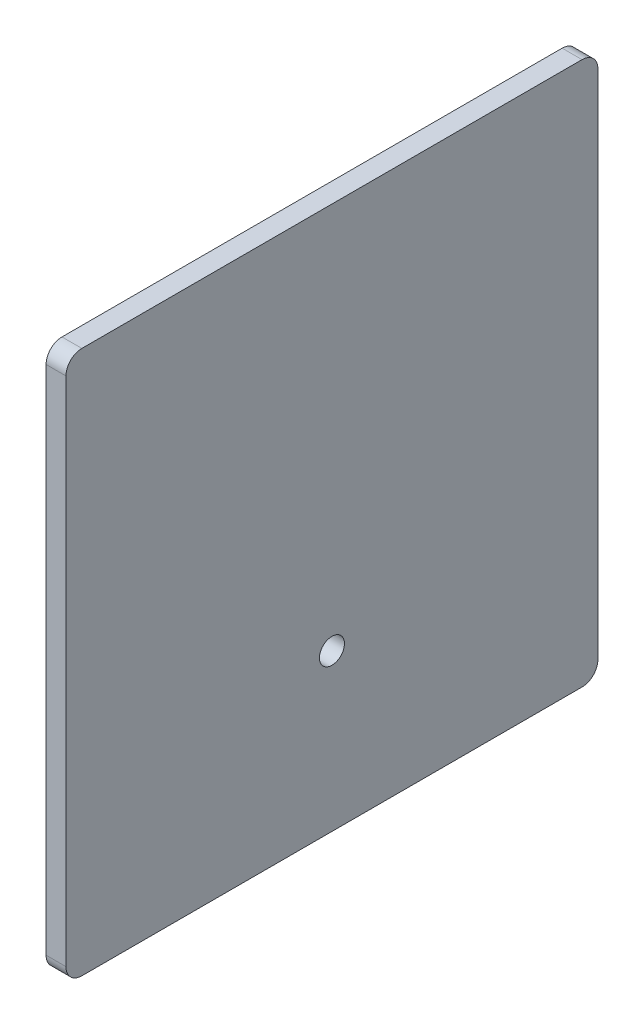
SolidWorks part; units mm, degrees
material "Acrylic (Medium-high impact)"
ref_plane "Front Plane" through (0, 0, 0) normal (0, 0, 1) x (1, 0, 0)
ref_plane "Top Plane" through (0, 0, 0) normal (0, 1, 0) x (1, 0, 0)
ref_plane "Right Plane" through (0, 0, 0) normal (1, 0, 0) x (0, 0, -1)
sketch "Sketch1" plane through (0, 0, 0) normal (1, 0, 0) x (0, 0, -1)
  line L1 (42.5, -43.4125) -> (-42.5, -43.4125)
  line L2 (42.5, -43.4125) -> (42.5, 43.4125)
  line L3 (42.5, 43.4125) -> (-42.5, 43.4125)
  line L4 (-42.5, -43.4125) -> (-42.5, 43.4125)
  line L5 (42.5, -43.4125) -> (-42.5, 43.4125) construction
  line L6 (42.5, 43.4125) -> (-42.5, -43.4125) construction
  point P0 (0, 0)
  dimension "D1" = 85
  dimension "D2" = 86.825
extrude "Boss-Extrude1" add sketch "Sketch1" along normal blind 3.175
sketch "Sketch2" plane through (3.175, 0, 0) normal (1, 0, 0) x (0, 0, -1)
  line L0 (-42.5, 43.4125) -> (-42.5, -43.4125) construction
  line L1 (-42.5, -43.4125) -> (42.5, -43.4125) construction
  circle A0 centre (0, -18.4125) radius 2
  dimension "D3" = 4
  dimension "D1" = 42.5
  dimension "D2" = 25
extrude "Cut-Extrude1" cut sketch "Sketch2" against normal through all
fillet "Fillet1" radius 2.54 4 edges at (1.5875, -43.4125, 42.5) (1.5875, -43.4125, -42.5) (1.5875, 43.4125, -42.5) (1.5875, 43.4125, 42.5)
